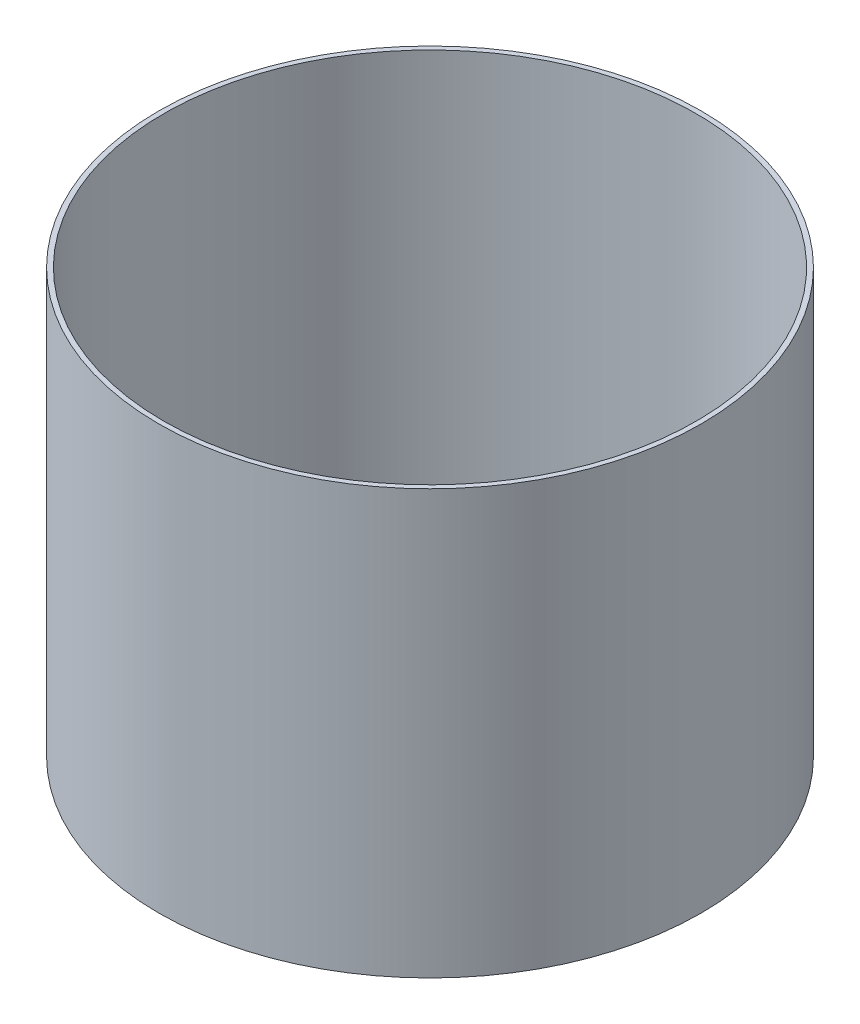
SolidWorks part; units mm, degrees
ref_plane "Front Plane" through (0, 0, 0) normal (0, 0, 1) x (1, 0, 0)
ref_plane "Top Plane" through (0, 0, 0) normal (0, 1, 0) x (1, 0, 0)
ref_plane "Right Plane" through (0, 0, 0) normal (1, 0, 0) x (0, 0, -1)
sketch "Sketch2" plane through (0, 0, 0) normal (0, 1, 0) x (1, 0, 0)
  circle A0 centre (0, 0) radius 71.12
  circle A1 centre (0, 0) radius 69.85
  dimension "D1" = 142.24
  dimension "D2" = 139.7
extrude "Extrude1" add sketch "Sketch2" against normal blind 111.125
sketch "Sketch1" plane through (0, 0, 0) normal (0, 0, 1) x (1, 0, 0)
  line L1 (-228.6, 0) -> (228.6, 0)
  line L2 (-228.6, 0) -> (-228.6, -99.6718)
  line L3 (-228.6, -99.6718) -> (228.6, -99.6718)
  line L4 (228.6, 0) -> (228.6, -99.6718)
  line L416 (-215.864, -82.9078) -> (215.864, -82.9078) construction
  line L417 (215.864, -82.9078) -> (215.864, -66.7382) construction
  line L418 (215.864, -66.7382) -> (-215.864, -66.7382) construction
  line L419 (-215.864, -66.7382) -> (-215.864, -82.9078) construction
  line L420 (-202.6925, -66.7382) -> (-201.5763, -66.7382) construction
  line L421 (-201.5763, -66.7382) -> (-201.5763, -57.5942) construction
  line L422 (-201.5763, -57.5942) -> (-202.6925, -57.5942) construction
  line L423 (-202.6925, -57.5942) -> (-202.6925, -66.7382) construction
  line L424 (-175.7412, -66.7382) -> (-174.6251, -66.7382) construction
  line L425 (-174.6251, -66.7382) -> (-174.6251, -57.5942) construction
  line L426 (-174.6251, -57.5942) -> (-175.7412, -57.5942) construction
  line L427 (-175.7412, -57.5942) -> (-175.7412, -66.7382) construction
  line L428 (-148.79, -66.7382) -> (-147.6738, -66.7382) construction
  line L429 (-147.6738, -66.7382) -> (-147.6738, -57.5942) construction
  line L430 (-147.6738, -57.5942) -> (-148.79, -57.5942) construction
  line L431 (-148.79, -57.5942) -> (-148.79, -66.7382) construction
  line L432 (-121.8387, -66.7382) -> (-120.7225, -66.7382) construction
  line L433 (-120.7225, -66.7382) -> (-120.7225, -57.5942) construction
  line L434 (-120.7225, -57.5942) -> (-121.8387, -57.5942) construction
  line L435 (-121.8387, -57.5942) -> (-121.8387, -66.7382) construction
  line L436 (-94.8875, -66.7382) -> (-93.7713, -66.7382) construction
  line L437 (-93.7713, -66.7382) -> (-93.7713, -57.5942) construction
  line L438 (-93.7713, -57.5942) -> (-94.8875, -57.5942) construction
  line L439 (-94.8875, -57.5942) -> (-94.8875, -66.7382) construction
  line L440 (-67.9362, -66.7382) -> (-66.82, -66.7382) construction
  line L441 (-66.82, -66.7382) -> (-66.82, -57.5942) construction
  line L442 (-66.82, -57.5942) -> (-67.9362, -57.5942) construction
  line L443 (-67.9362, -57.5942) -> (-67.9362, -66.7382) construction
  line L444 (-40.985, -66.7382) -> (-39.8688, -66.7382) construction
  line L445 (-39.8688, -66.7382) -> (-39.8688, -57.5942) construction
  line L446 (-39.8688, -57.5942) -> (-40.985, -57.5942) construction
  line L447 (-40.985, -57.5942) -> (-40.985, -66.7382) construction
  line L448 (-14.0337, -66.7382) -> (-12.9175, -66.7382) construction
  line L449 (-12.9175, -66.7382) -> (-12.9175, -57.5942) construction
  line L450 (-12.9175, -57.5942) -> (-14.0337, -57.5942) construction
  line L451 (-14.0337, -57.5942) -> (-14.0337, -66.7382) construction
  line L452 (12.9175, -66.7382) -> (14.0337, -66.7382) construction
  line L453 (14.0337, -66.7382) -> (14.0337, -57.5942) construction
  line L454 (14.0337, -57.5942) -> (12.9175, -57.5942) construction
  line L455 (12.9175, -57.5942) -> (12.9175, -66.7382) construction
  line L456 (39.8688, -66.7382) -> (40.985, -66.7382) construction
  line L457 (40.985, -66.7382) -> (40.985, -57.5942) construction
  line L458 (40.985, -57.5942) -> (39.8688, -57.5942) construction
  line L459 (39.8688, -57.5942) -> (39.8688, -66.7382) construction
  line L460 (66.82, -66.7382) -> (67.9362, -66.7382) construction
  line L461 (67.9362, -66.7382) -> (67.9362, -57.5942) construction
  line L462 (67.9362, -57.5942) -> (66.82, -57.5942) construction
  line L463 (66.82, -57.5942) -> (66.82, -66.7382) construction
  line L464 (93.7713, -66.7382) -> (94.8875, -66.7382) construction
  line L465 (94.8875, -66.7382) -> (94.8875, -57.5942) construction
  line L466 (94.8875, -57.5942) -> (93.7713, -57.5942) construction
  line L467 (93.7713, -57.5942) -> (93.7713, -66.7382) construction
  line L468 (120.7225, -66.7382) -> (121.8387, -66.7382) construction
  line L469 (121.8387, -66.7382) -> (121.8387, -57.5942) construction
  line L470 (121.8387, -57.5942) -> (120.7225, -57.5942) construction
  line L471 (120.7225, -57.5942) -> (120.7225, -66.7382) construction
  line L472 (147.6738, -66.7382) -> (148.79, -66.7382) construction
  line L473 (148.79, -66.7382) -> (148.79, -57.5942) construction
  line L474 (148.79, -57.5942) -> (147.6738, -57.5942) construction
  line L475 (147.6738, -57.5942) -> (147.6738, -66.7382) construction
  line L476 (174.6251, -66.7382) -> (175.7412, -66.7382) construction
  line L477 (175.7412, -66.7382) -> (175.7412, -57.5942) construction
  line L478 (175.7412, -57.5942) -> (174.6251, -57.5942) construction
  line L479 (174.6251, -57.5942) -> (174.6251, -66.7382) construction
  line L480 (201.5763, -66.7382) -> (202.6925, -66.7382) construction
  line L481 (202.6925, -66.7382) -> (202.6925, -57.5942) construction
  line L482 (202.6925, -57.5942) -> (201.5763, -57.5942) construction
  line L483 (201.5763, -57.5942) -> (201.5763, -66.7382) construction
  line L484 (-201.5763, -57.5942) -> (-175.7412, -57.5942) construction
  line L485 (-175.7412, -57.5942) -> (-175.7412, -56.478) construction
  line L486 (-175.7412, -56.478) -> (-201.5763, -56.478) construction
  line L487 (-201.5763, -56.478) -> (-201.5763, -57.5942) construction
  line L488 (-147.6738, -57.5942) -> (-121.8387, -57.5942) construction
  line L489 (-121.8387, -57.5942) -> (-121.8387, -56.478) construction
  line L490 (-121.8387, -56.478) -> (-147.6738, -56.478) construction
  line L491 (-147.6738, -56.478) -> (-147.6738, -57.5942) construction
  line L492 (-93.7713, -57.5942) -> (-67.9361, -57.5942) construction
  line L493 (-67.9361, -57.5942) -> (-67.9361, -56.478) construction
  line L494 (-67.9361, -56.478) -> (-93.7713, -56.478) construction
  line L495 (-93.7713, -56.478) -> (-93.7713, -57.5942) construction
  line L496 (-39.8687, -57.5942) -> (-14.0336, -57.5942) construction
  line L497 (-14.0336, -57.5942) -> (-14.0336, -56.478) construction
  line L498 (-14.0336, -56.478) -> (-39.8687, -56.478) construction
  line L499 (-39.8687, -56.478) -> (-39.8687, -57.5942) construction
  line L500 (14.0336, -57.5942) -> (39.8687, -57.5942) construction
  line L501 (39.8687, -57.5942) -> (39.8687, -56.478) construction
  line L502 (39.8687, -56.478) -> (14.0336, -56.478) construction
  line L503 (14.0336, -56.478) -> (14.0336, -57.5942) construction
  line L504 (67.9361, -57.5942) -> (93.7713, -57.5942) construction
  line L505 (93.7713, -57.5942) -> (93.7713, -56.478) construction
  line L506 (93.7713, -56.478) -> (67.9361, -56.478) construction
  line L507 (67.9361, -56.478) -> (67.9361, -57.5942) construction
  line L508 (121.8387, -57.5942) -> (147.6738, -57.5942) construction
  line L509 (147.6738, -57.5942) -> (147.6738, -56.478) construction
  line L510 (147.6738, -56.478) -> (121.8387, -56.478) construction
  line L511 (121.8387, -56.478) -> (121.8387, -57.5942) construction
  line L512 (175.7412, -57.5942) -> (201.5763, -57.5942) construction
  line L513 (201.5763, -57.5942) -> (201.5763, -56.478) construction
  line L514 (201.5763, -56.478) -> (175.7412, -56.478) construction
  line L515 (175.7412, -56.478) -> (175.7412, -57.5942) construction
  line L516 (-190.8513, -57.5942) -> (-186.4661, -57.5942) construction
  line L517 (-186.4661, -57.5942) -> (-186.4661, -47.334) construction
  line L518 (-186.4661, -47.334) -> (-190.8513, -47.334) construction
  line L519 (-190.8513, -47.334) -> (-190.8513, -57.5942) construction
  line L520 (-136.9488, -57.5942) -> (-132.5636, -57.5942) construction
  line L521 (-132.5636, -57.5942) -> (-132.5636, -47.334) construction
  line L522 (-132.5636, -47.334) -> (-136.9488, -47.334) construction
  line L523 (-136.9488, -47.334) -> (-136.9488, -57.5942) construction
  line L524 (-83.0464, -57.5942) -> (-78.6611, -57.5942) construction
  line L525 (-78.6611, -57.5942) -> (-78.6611, -47.334) construction
  line L526 (-78.6611, -47.334) -> (-83.0464, -47.334) construction
  line L527 (-83.0464, -47.334) -> (-83.0464, -57.5942) construction
  line L528 (-29.1439, -57.5942) -> (-24.7585, -57.5942) construction
  line L529 (-24.7585, -57.5942) -> (-24.7585, -47.334) construction
  line L530 (-24.7585, -47.334) -> (-29.1439, -47.334) construction
  line L531 (-29.1439, -47.334) -> (-29.1439, -57.5942) construction
  line L532 (24.7585, -57.5942) -> (29.1439, -57.5942) construction
  line L533 (29.1439, -57.5942) -> (29.1439, -47.334) construction
  line L534 (29.1439, -47.334) -> (24.7585, -47.334) construction
  line L535 (24.7585, -47.334) -> (24.7585, -57.5942) construction
  line L536 (78.6611, -57.5942) -> (83.0464, -57.5942) construction
  line L537 (83.0464, -57.5942) -> (83.0464, -47.334) construction
  line L538 (83.0464, -47.334) -> (78.6611, -47.334) construction
  line L539 (78.6611, -47.334) -> (78.6611, -57.5942) construction
  line L540 (132.5636, -57.5942) -> (136.9488, -57.5942) construction
  line L541 (136.9488, -57.5942) -> (136.9488, -47.334) construction
  line L542 (136.9488, -47.334) -> (132.5636, -47.334) construction
  line L543 (132.5636, -47.334) -> (132.5636, -57.5942) construction
  line L544 (186.4661, -57.5942) -> (190.8513, -57.5942) construction
  line L545 (190.8513, -57.5942) -> (190.8513, -47.334) construction
  line L546 (190.8513, -47.334) -> (186.4661, -47.334) construction
  line L547 (186.4661, -47.334) -> (186.4661, -57.5942) construction
  line L548 (-186.466, -47.334) -> (-177.9096, -47.334) construction
  line L549 (-177.9096, -47.334) -> (-177.9096, -42.9487) construction
  line L550 (-177.9096, -42.9487) -> (-186.466, -42.9487) construction
  line L551 (-186.466, -42.9487) -> (-186.466, -47.334) construction
  line L552 (-145.5055, -47.334) -> (-136.9489, -47.334) construction
  line L553 (-136.9489, -47.334) -> (-136.9489, -42.9487) construction
  line L554 (-136.9489, -42.9487) -> (-145.5055, -42.9487) construction
  line L555 (-145.5055, -42.9487) -> (-145.5055, -47.334) construction
  line L556 (-78.6611, -47.334) -> (-70.1045, -47.334) construction
  line L557 (-70.1045, -47.334) -> (-70.1045, -42.9487) construction
  line L558 (-70.1045, -42.9487) -> (-78.6611, -42.9487) construction
  line L559 (-78.6611, -42.9487) -> (-78.6611, -47.334) construction
  line L560 (-37.7005, -47.334) -> (-29.1439, -47.334) construction
  line L561 (-29.1439, -47.334) -> (-29.1439, -42.9487) construction
  line L562 (-29.1439, -42.9487) -> (-37.7005, -42.9487) construction
  line L563 (-37.7005, -42.9487) -> (-37.7005, -47.334) construction
  line L564 (29.1439, -47.334) -> (37.7005, -47.334) construction
  line L565 (37.7005, -47.334) -> (37.7005, -42.9487) construction
  line L566 (37.7005, -42.9487) -> (29.1439, -42.9487) construction
  line L567 (29.1439, -42.9487) -> (29.1439, -47.334) construction
  line L568 (70.1045, -47.334) -> (78.6611, -47.334) construction
  line L569 (78.6611, -47.334) -> (78.6611, -42.9487) construction
  line L570 (78.6611, -42.9487) -> (70.1045, -42.9487) construction
  line L571 (70.1045, -42.9487) -> (70.1045, -47.334) construction
  line L572 (136.9489, -47.334) -> (145.5055, -47.334) construction
  line L573 (145.5055, -47.334) -> (145.5055, -42.9487) construction
  line L574 (145.5055, -42.9487) -> (136.9489, -42.9487) construction
  line L575 (136.9489, -42.9487) -> (136.9489, -47.334) construction
  line L576 (177.9096, -47.334) -> (186.466, -47.334) construction
  line L577 (186.466, -47.334) -> (186.466, -42.9487) construction
  line L578 (186.466, -42.9487) -> (177.9096, -42.9487) construction
  line L579 (177.9096, -42.9487) -> (177.9096, -47.334) construction
  line L580 (-177.9095, -46.538) -> (-168.0714, -46.538) construction
  line L581 (-168.0714, -46.538) -> (-168.0714, -43.7446) construction
  line L582 (-168.0714, -43.7446) -> (-177.9095, -43.7446) construction
  line L583 (-177.9095, -43.7446) -> (-177.9095, -46.538) construction
  line L584 (-155.3435, -46.538) -> (-145.5054, -46.538) construction
  line L585 (-145.5054, -46.538) -> (-145.5054, -43.7446) construction
  line L586 (-145.5054, -43.7446) -> (-155.3435, -43.7446) construction
  line L587 (-155.3435, -43.7446) -> (-155.3435, -46.538) construction
  line L588 (-70.1045, -46.538) -> (-60.2665, -46.538) construction
  line L589 (-60.2665, -46.538) -> (-60.2665, -43.7446) construction
  line L590 (-60.2665, -43.7446) -> (-70.1045, -43.7446) construction
  line L591 (-70.1045, -43.7446) -> (-70.1045, -46.538) construction
  line L592 (-47.5385, -46.538) -> (-37.7005, -46.538) construction
  line L593 (-37.7005, -46.538) -> (-37.7005, -43.7446) construction
  line L594 (-37.7005, -43.7446) -> (-47.5385, -43.7446) construction
  line L595 (-47.5385, -43.7446) -> (-47.5385, -46.538) construction
  line L596 (37.7005, -46.538) -> (47.5385, -46.538) construction
  line L597 (47.5385, -46.538) -> (47.5385, -43.7446) construction
  line L598 (47.5385, -43.7446) -> (37.7005, -43.7446) construction
  line L599 (37.7005, -43.7446) -> (37.7005, -46.538) construction
  line L600 (60.2665, -46.538) -> (70.1045, -46.538) construction
  line L601 (70.1045, -46.538) -> (70.1045, -43.7446) construction
  line L602 (70.1045, -43.7446) -> (60.2665, -43.7446) construction
  line L603 (60.2665, -43.7446) -> (60.2665, -46.538) construction
  line L604 (145.5054, -46.538) -> (155.3435, -46.538) construction
  line L605 (155.3435, -46.538) -> (155.3435, -43.7446) construction
  line L606 (155.3435, -43.7446) -> (145.5054, -43.7446) construction
  line L607 (145.5054, -43.7446) -> (145.5054, -46.538) construction
  line L608 (168.0714, -46.538) -> (177.9095, -46.538) construction
  line L609 (177.9095, -46.538) -> (177.9095, -43.7446) construction
  line L610 (177.9095, -43.7446) -> (168.0714, -43.7446) construction
  line L611 (168.0714, -43.7446) -> (168.0714, -46.538) construction
  line L612 (-168.0714, -45.9607) -> (-155.3436, -45.9607) construction
  line L613 (-155.3436, -45.9607) -> (-155.3436, -44.322) construction
  line L614 (-155.3436, -44.322) -> (-168.0714, -44.322) construction
  line L615 (-168.0714, -44.322) -> (-168.0714, -45.9607) construction
  line L616 (-60.2665, -45.9607) -> (-47.5385, -45.9607) construction
  line L617 (-47.5385, -45.9607) -> (-47.5385, -44.322) construction
  line L618 (-47.5385, -44.322) -> (-60.2665, -44.322) construction
  line L619 (-60.2665, -44.322) -> (-60.2665, -45.9607) construction
  line L620 (47.5385, -45.9607) -> (60.2665, -45.9607) construction
  line L621 (60.2665, -45.9607) -> (60.2665, -44.322) construction
  line L622 (60.2665, -44.322) -> (47.5385, -44.322) construction
  line L623 (47.5385, -44.322) -> (47.5385, -45.9607) construction
  line L624 (155.3436, -45.9607) -> (168.0714, -45.9607) construction
  line L625 (168.0714, -45.9607) -> (168.0714, -44.322) construction
  line L626 (168.0714, -44.322) -> (155.3436, -44.322) construction
  line L627 (155.3436, -44.322) -> (155.3436, -45.9607) construction
  line L628 (-164.5244, -44.322) -> (-158.8906, -44.322) construction
  line L629 (-158.8906, -44.322) -> (-158.8906, -35.178) construction
  line L630 (-158.8906, -35.178) -> (-164.5244, -35.178) construction
  line L631 (-164.5244, -35.178) -> (-164.5244, -44.322) construction
  line L632 (-56.7194, -44.322) -> (-51.0856, -44.322) construction
  line L633 (-51.0856, -44.322) -> (-51.0856, -35.178) construction
  line L634 (-51.0856, -35.178) -> (-56.7194, -35.178) construction
  line L635 (-56.7194, -35.178) -> (-56.7194, -44.322) construction
  line L636 (51.0856, -44.322) -> (56.7194, -44.322) construction
  line L637 (56.7194, -44.322) -> (56.7194, -35.178) construction
  line L638 (56.7194, -35.178) -> (51.0856, -35.178) construction
  line L639 (51.0856, -35.178) -> (51.0856, -44.322) construction
  line L640 (158.8906, -44.322) -> (164.5244, -44.322) construction
  line L641 (164.5244, -44.322) -> (164.5244, -35.178) construction
  line L642 (164.5244, -35.178) -> (158.8906, -35.178) construction
  line L643 (158.8906, -35.178) -> (158.8906, -44.322) construction
  line L644 (-158.8906, -35.178) -> (-131.3922, -35.178) construction
  line L645 (-131.3922, -35.178) -> (-131.3922, -29.5443) construction
  line L646 (-131.3922, -29.5443) -> (-158.8906, -29.5443) construction
  line L647 (-158.8906, -29.5443) -> (-158.8906, -35.178) construction
  line L648 (-84.2178, -35.178) -> (-56.7194, -35.178) construction
  line L649 (-56.7194, -35.178) -> (-56.7194, -29.5443) construction
  line L650 (-56.7194, -29.5443) -> (-84.2178, -29.5443) construction
  line L651 (-84.2178, -29.5443) -> (-84.2178, -35.178) construction
  line L652 (56.7194, -35.178) -> (84.2178, -35.178) construction
  line L653 (84.2178, -35.178) -> (84.2178, -29.5443) construction
  line L654 (84.2178, -29.5443) -> (56.7194, -29.5443) construction
  line L655 (56.7194, -29.5443) -> (56.7194, -35.178) construction
  line L656 (131.3922, -35.178) -> (158.8906, -35.178) construction
  line L657 (158.8906, -35.178) -> (158.8906, -29.5443) construction
  line L658 (158.8906, -29.5443) -> (131.3922, -29.5443) construction
  line L659 (131.3922, -29.5443) -> (131.3922, -35.178) construction
  line L660 (-131.3922, -33.9769) -> (-121.3448, -33.9769) construction
  line L661 (-121.3448, -33.9769) -> (-121.3448, -30.7453) construction
  line L662 (-121.3448, -30.7453) -> (-131.3922, -30.7453) construction
  line L663 (-131.3922, -30.7453) -> (-131.3922, -33.9769) construction
  line L664 (-94.2652, -33.9769) -> (-84.2178, -33.9769) construction
  line L665 (-84.2178, -33.9769) -> (-84.2178, -30.7453) construction
  line L666 (-84.2178, -30.7453) -> (-94.2652, -30.7453) construction
  line L667 (-94.2652, -30.7453) -> (-94.2652, -33.9769) construction
  line L668 (84.2178, -33.9769) -> (94.2652, -33.9769) construction
  line L669 (94.2652, -33.9769) -> (94.2652, -30.7453) construction
  line L670 (94.2652, -30.7453) -> (84.2178, -30.7453) construction
  line L671 (84.2178, -30.7453) -> (84.2178, -33.9769) construction
  line L672 (121.3448, -33.9769) -> (131.3922, -33.9769) construction
  line L673 (131.3922, -33.9769) -> (131.3922, -30.7453) construction
  line L674 (131.3922, -30.7453) -> (121.3448, -30.7453) construction
  line L675 (121.3448, -30.7453) -> (121.3448, -33.9769) construction
  line L676 (-121.3448, -33.1804) -> (-94.2652, -33.1804) construction
  line L677 (-94.2652, -33.1804) -> (-94.2652, -31.5418) construction
  line L678 (-94.2652, -31.5418) -> (-121.3448, -31.5418) construction
  line L679 (-121.3448, -31.5418) -> (-121.3448, -33.1804) construction
  line L680 (94.2652, -33.1804) -> (121.3448, -33.1804) construction
  line L681 (121.3448, -33.1804) -> (121.3448, -31.5418) construction
  line L682 (121.3448, -31.5418) -> (94.2652, -31.5418) construction
  line L683 (94.2652, -31.5418) -> (94.2652, -33.1804) construction
  line L684 (-110.6219, -31.5418) -> (-104.9881, -31.5418) construction
  line L685 (-104.9881, -31.5418) -> (-104.9881, -22.3978) construction
  line L686 (-104.9881, -22.3978) -> (-110.6219, -22.3978) construction
  line L687 (-110.6219, -22.3978) -> (-110.6219, -31.5418) construction
  line L688 (104.9881, -31.5418) -> (110.6219, -31.5418) construction
  line L689 (110.6219, -31.5418) -> (110.6219, -22.3978) construction
  line L690 (110.6219, -22.3978) -> (104.9881, -22.3978) construction
  line L691 (104.9881, -22.3978) -> (104.9881, -31.5418) construction
  line L692 (-104.9881, -22.3978) -> (-41.5547, -22.3978) construction
  line L693 (-41.5547, -22.3978) -> (-41.5547, -16.764) construction
  line L694 (-41.5547, -16.764) -> (-104.9881, -16.764) construction
  line L695 (-104.9881, -16.764) -> (-104.9881, -22.3978) construction
  line L696 (41.5547, -22.3978) -> (104.9881, -22.3978) construction
  line L697 (104.9881, -22.3978) -> (104.9881, -16.764) construction
  line L698 (104.9881, -16.764) -> (41.5547, -16.764) construction
  line L699 (41.5547, -16.764) -> (41.5547, -22.3978) construction
  line L700 (-41.5547, -21.1967) -> (-31.5072, -21.1967) construction
  line L701 (-31.5072, -21.1967) -> (-31.5072, -17.9651) construction
  line L702 (-31.5072, -17.9651) -> (-41.5547, -17.9651) construction
  line L703 (-41.5547, -17.9651) -> (-41.5547, -21.1967) construction
  line L704 (31.5072, -21.1967) -> (41.5547, -21.1967) construction
  line L705 (41.5547, -21.1967) -> (41.5547, -17.9651) construction
  line L706 (41.5547, -17.9651) -> (31.5072, -17.9651) construction
  line L707 (31.5072, -17.9651) -> (31.5072, -21.1967) construction
  line L708 (-31.5073, -20.4003) -> (31.5073, -20.4003) construction
  line L709 (31.5073, -20.4003) -> (31.5073, -18.7616) construction
  line L710 (31.5073, -18.7616) -> (-31.5073, -18.7616) construction
  line L711 (-31.5073, -18.7616) -> (-31.5073, -20.4003) construction
  line L712 (-202.1344, -57.5942) -> (-201.5762, -57.5942) construction
  line L713 (-201.5762, -57.5942) -> (-201.5762, -57.0361) construction
  line L714 (-201.5762, -57.0361) -> (-202.1344, -57.0361) construction
  line L715 (-202.1344, -57.0361) -> (-202.1344, -57.5942) construction
  line L716 (-175.7412, -57.5942) -> (-175.183, -57.5942) construction
  line L717 (-175.183, -57.5942) -> (-175.183, -57.0361) construction
  line L718 (-175.183, -57.0361) -> (-175.7412, -57.0361) construction
  line L719 (-175.7412, -57.0361) -> (-175.7412, -57.5942) construction
  line L720 (-148.2319, -57.5942) -> (-147.6737, -57.5942) construction
  line L721 (-147.6737, -57.5942) -> (-147.6737, -57.0361) construction
  line L722 (-147.6737, -57.0361) -> (-148.2319, -57.0361) construction
  line L723 (-148.2319, -57.0361) -> (-148.2319, -57.5942) construction
  line L724 (-121.8387, -57.5942) -> (-121.2806, -57.5942) construction
  line L725 (-121.2806, -57.5942) -> (-121.2806, -57.0361) construction
  line L726 (-121.2806, -57.0361) -> (-121.8387, -57.0361) construction
  line L727 (-121.8387, -57.0361) -> (-121.8387, -57.5942) construction
  line L728 (-94.3293, -57.5942) -> (-93.7712, -57.5942) construction
  line L729 (-93.7712, -57.5942) -> (-93.7712, -57.0361) construction
  line L730 (-93.7712, -57.0361) -> (-94.3293, -57.0361) construction
  line L731 (-94.3293, -57.0361) -> (-94.3293, -57.5942) construction
  line L732 (-67.9361, -57.5942) -> (-67.3781, -57.5942) construction
  line L733 (-67.3781, -57.5942) -> (-67.3781, -57.0361) construction
  line L734 (-67.3781, -57.0361) -> (-67.9361, -57.0361) construction
  line L735 (-67.9361, -57.0361) -> (-67.9361, -57.5942) construction
  line L736 (-40.4268, -57.5942) -> (-39.8687, -57.5942) construction
  line L737 (-39.8687, -57.5942) -> (-39.8687, -57.0361) construction
  line L738 (-39.8687, -57.0361) -> (-40.4268, -57.0361) construction
  line L739 (-40.4268, -57.0361) -> (-40.4268, -57.5942) construction
  line L740 (-14.0336, -57.5942) -> (-13.4756, -57.5942) construction
  line L741 (-13.4756, -57.5942) -> (-13.4756, -57.0361) construction
  line L742 (-13.4756, -57.0361) -> (-14.0336, -57.0361) construction
  line L743 (-14.0336, -57.0361) -> (-14.0336, -57.5942) construction
  line L744 (13.4756, -57.5942) -> (14.0336, -57.5942) construction
  line L745 (14.0336, -57.5942) -> (14.0336, -57.0361) construction
  line L746 (14.0336, -57.0361) -> (13.4756, -57.0361) construction
  line L747 (13.4756, -57.0361) -> (13.4756, -57.5942) construction
  line L748 (39.8687, -57.5942) -> (40.4268, -57.5942) construction
  line L749 (40.4268, -57.5942) -> (40.4268, -57.0361) construction
  line L750 (40.4268, -57.0361) -> (39.8687, -57.0361) construction
  line L751 (39.8687, -57.0361) -> (39.8687, -57.5942) construction
  line L752 (67.3781, -57.5942) -> (67.9361, -57.5942) construction
  line L753 (67.9361, -57.5942) -> (67.9361, -57.0361) construction
  line L754 (67.9361, -57.0361) -> (67.3781, -57.0361) construction
  line L755 (67.3781, -57.0361) -> (67.3781, -57.5942) construction
  line L756 (93.7712, -57.5942) -> (94.3293, -57.5942) construction
  line L757 (94.3293, -57.5942) -> (94.3293, -57.0361) construction
  line L758 (94.3293, -57.0361) -> (93.7712, -57.0361) construction
  line L759 (93.7712, -57.0361) -> (93.7712, -57.5942) construction
  line L760 (121.2806, -57.5942) -> (121.8387, -57.5942) construction
  line L761 (121.8387, -57.5942) -> (121.8387, -57.0361) construction
  line L762 (121.8387, -57.0361) -> (121.2806, -57.0361) construction
  line L763 (121.2806, -57.0361) -> (121.2806, -57.5942) construction
  line L764 (147.6737, -57.5942) -> (148.2319, -57.5942) construction
  line L765 (148.2319, -57.5942) -> (148.2319, -57.0361) construction
  line L766 (148.2319, -57.0361) -> (147.6737, -57.0361) construction
  line L767 (147.6737, -57.0361) -> (147.6737, -57.5942) construction
  line L768 (175.183, -57.5942) -> (175.7412, -57.5942) construction
  line L769 (175.7412, -57.5942) -> (175.7412, -57.0361) construction
  line L770 (175.7412, -57.0361) -> (175.183, -57.0361) construction
  line L771 (175.183, -57.0361) -> (175.183, -57.5942) construction
  line L772 (201.5762, -57.5942) -> (202.1344, -57.5942) construction
  line L773 (202.1344, -57.5942) -> (202.1344, -57.0361) construction
  line L774 (202.1344, -57.0361) -> (201.5762, -57.0361) construction
  line L775 (201.5762, -57.0361) -> (201.5762, -57.5942) construction
  line L776 (-188.6588, -47.334) -> (-186.466, -47.334) construction
  line L777 (-186.466, -47.334) -> (-186.466, -45.1412) construction
  line L778 (-186.466, -45.1412) -> (-188.6588, -45.1412) construction
  line L779 (-188.6588, -45.1412) -> (-188.6588, -47.334) construction
  line L780 (-136.9489, -47.334) -> (-134.7563, -47.334) construction
  line L781 (-134.7563, -47.334) -> (-134.7563, -45.1412) construction
  line L782 (-134.7563, -45.1412) -> (-136.9489, -45.1412) construction
  line L783 (-136.9489, -45.1412) -> (-136.9489, -47.334) construction
  line L784 (-80.8538, -47.334) -> (-78.6611, -47.334) construction
  line L785 (-78.6611, -47.334) -> (-78.6611, -45.1412) construction
  line L786 (-78.6611, -45.1412) -> (-80.8538, -45.1412) construction
  line L787 (-80.8538, -45.1412) -> (-80.8538, -47.334) construction
  line L788 (-29.1439, -47.334) -> (-26.9513, -47.334) construction
  line L789 (-26.9513, -47.334) -> (-26.9513, -45.1412) construction
  line L790 (-26.9513, -45.1412) -> (-29.1439, -45.1412) construction
  line L791 (-29.1439, -45.1412) -> (-29.1439, -47.334) construction
  line L792 (26.9513, -47.334) -> (29.1439, -47.334) construction
  line L793 (29.1439, -47.334) -> (29.1439, -45.1412) construction
  line L794 (29.1439, -45.1412) -> (26.9513, -45.1412) construction
  line L795 (26.9513, -45.1412) -> (26.9513, -47.334) construction
  line L796 (78.6611, -47.334) -> (80.8538, -47.334) construction
  line L797 (80.8538, -47.334) -> (80.8538, -45.1412) construction
  line L798 (80.8538, -45.1412) -> (78.6611, -45.1412) construction
  line L799 (78.6611, -45.1412) -> (78.6611, -47.334) construction
  line L800 (134.7563, -47.334) -> (136.9489, -47.334) construction
  line L801 (136.9489, -47.334) -> (136.9489, -45.1412) construction
  line L802 (136.9489, -45.1412) -> (134.7563, -45.1412) construction
  line L803 (134.7563, -45.1412) -> (134.7563, -47.334) construction
  line L804 (186.466, -47.334) -> (188.6588, -47.334) construction
  line L805 (188.6588, -47.334) -> (188.6588, -45.1412) construction
  line L806 (188.6588, -45.1412) -> (186.466, -45.1412) construction
  line L807 (186.466, -45.1412) -> (186.466, -47.334) construction
  line L808 (-161.7074, -35.178) -> (-158.8906, -35.178) construction
  line L809 (-158.8906, -35.178) -> (-158.8906, -32.3611) construction
  line L810 (-158.8906, -32.3611) -> (-161.7074, -32.3611) construction
  line L811 (-161.7074, -32.3611) -> (-161.7074, -35.178) construction
  line L812 (-56.7193, -35.178) -> (-53.9024, -35.178) construction
  line L813 (-53.9024, -35.178) -> (-53.9024, -32.3611) construction
  line L814 (-53.9024, -32.3611) -> (-56.7193, -32.3611) construction
  line L815 (-56.7193, -32.3611) -> (-56.7193, -35.178) construction
  line L816 (53.9024, -35.178) -> (56.7193, -35.178) construction
  line L817 (56.7193, -35.178) -> (56.7193, -32.3611) construction
  line L818 (56.7193, -32.3611) -> (53.9024, -32.3611) construction
  line L819 (53.9024, -32.3611) -> (53.9024, -35.178) construction
  line L820 (158.8906, -35.178) -> (161.7074, -35.178) construction
  line L821 (161.7074, -35.178) -> (161.7074, -32.3611) construction
  line L822 (161.7074, -32.3611) -> (158.8906, -32.3611) construction
  line L823 (158.8906, -32.3611) -> (158.8906, -35.178) construction
  line L824 (-107.805, -22.3977) -> (-104.9881, -22.3977) construction
  line L825 (-104.9881, -22.3977) -> (-104.9881, -19.5809) construction
  line L826 (-104.9881, -19.5809) -> (-107.805, -19.5809) construction
  line L827 (-107.805, -19.5809) -> (-107.805, -22.3977) construction
  line L828 (104.9881, -22.3977) -> (107.805, -22.3977) construction
  line L829 (107.805, -22.3977) -> (107.805, -19.5809) construction
  line L830 (107.805, -19.5809) -> (104.9881, -19.5809) construction
  line L831 (104.9881, -19.5809) -> (104.9881, -22.3977) construction
  line L832 (-228.6, 0) -> (228.6, 0) construction
  line L866 (-228.6, -99.6718) -> (228.6, -99.6718) construction
  line L867 (-228.6, 0) -> (228.6, 0) construction
  line L868 (218.15, -9.144) -> (218.15, -57.5942) construction
  line L869 (-218.15, -9.144) -> (-218.15, -57.5942) construction
  line L870 (-202.4134, -57.5942) -> (-201.5763, -56.757) construction
  line L871 (-175.7412, -56.757) -> (-174.9041, -57.5942) construction
  line L872 (-148.5109, -57.5942) -> (-147.6738, -56.757) construction
  line L873 (-121.8387, -56.757) -> (-121.0016, -57.5942) construction
  line L874 (-94.6084, -57.5942) -> (-93.7713, -56.757) construction
  line L875 (-67.9362, -56.757) -> (-67.0991, -57.5942) construction
  line L876 (-40.7059, -57.5942) -> (-39.8688, -56.757) construction
  line L877 (-14.0337, -56.757) -> (-13.1966, -57.5942) construction
  line L878 (13.1966, -57.5942) -> (14.0337, -56.757) construction
  line L879 (39.8688, -56.757) -> (40.7059, -57.5942) construction
  line L880 (67.0991, -57.5942) -> (67.9362, -56.757) construction
  line L881 (93.7713, -56.757) -> (94.6084, -57.5942) construction
  line L882 (121.0016, -57.5942) -> (121.8387, -56.757) construction
  line L883 (147.6738, -56.757) -> (148.5109, -57.5942) construction
  line L884 (174.9041, -57.5942) -> (175.7412, -56.757) construction
  line L885 (201.5763, -56.757) -> (202.4134, -57.5942) construction
  line L886 (-189.7551, -47.334) -> (-186.4661, -44.045) construction
  line L887 (-136.9489, -44.045) -> (-133.66, -47.334) construction
  line L888 (-81.9501, -47.334) -> (-78.6611, -44.045) construction
  line L889 (-29.1439, -44.045) -> (-25.8549, -47.334) construction
  line L890 (25.8549, -47.334) -> (29.1439, -44.045) construction
  line L891 (78.6611, -44.045) -> (81.9501, -47.334) construction
  line L892 (133.66, -47.334) -> (136.9489, -44.045) construction
  line L893 (186.4661, -44.045) -> (189.7551, -47.334) construction
  line L894 (-163.116, -35.178) -> (-158.8906, -30.9527) construction
  line L895 (-56.7194, -30.9527) -> (-52.4941, -35.178) construction
  line L896 (52.4941, -35.178) -> (56.7194, -30.9527) construction
  line L897 (158.8906, -30.9527) -> (163.116, -35.178) construction
  line L898 (-109.2134, -22.3978) -> (-104.9881, -18.1725) construction
  line L899 (104.9881, -18.1725) -> (109.2134, -22.3978) construction
  circle A25 centre (210.53, -94.5918) radius 2.54 construction
  circle A26 centre (107.805, -94.5918) radius 2.54 construction
  circle A27 centre (0, -94.5918) radius 2.54 construction
  circle A28 centre (-107.805, -94.5918) radius 2.54 construction
  circle A29 centre (-210.53, -94.5918) radius 2.54 construction
  circle A30 centre (210.53, -5.08) radius 2.54 construction
  circle A31 centre (107.805, -5.08) radius 2.54 construction
  circle A32 centre (0, -5.08) radius 2.54 construction
  circle A33 centre (-107.805, -5.08) radius 2.54 construction
  circle A34 centre (-210.53, -5.08) radius 2.54 construction
  circle A35 centre (210.53, -49.8359) radius 2.54 construction
  circle A36 centre (-210.53, -49.8359) radius 2.54 construction
  circle A37 centre (0, -19.5809) radius 6.35 construction
  circle A38 centre (210.53, -94.5918) radius 1.1303 construction
  circle A39 centre (107.805, -94.5918) radius 1.1303 construction
  circle A40 centre (0, -94.5918) radius 1.1303 construction
  circle A41 centre (-107.805, -94.5918) radius 1.1303 construction
  circle A42 centre (-210.53, -94.5918) radius 1.1303 construction
  circle A43 centre (210.53, -5.08) radius 1.1303 construction
  circle A44 centre (107.805, -5.08) radius 1.1303 construction
  circle A45 centre (0, -5.08) radius 1.1303 construction
  circle A46 centre (-107.805, -5.08) radius 1.1303 construction
  circle A47 centre (-210.53, -5.08) radius 1.1303 construction
  circle A48 centre (210.53, -49.8359) radius 1.1303 construction
  circle A49 centre (-210.53, -49.8359) radius 1.1303 construction
  circle A62 centre (210.53, -94.5918) radius 0.635 construction
  circle A63 centre (107.805, -94.5918) radius 0.635 construction
  circle A64 centre (0, -94.5918) radius 0.635 construction
  circle A65 centre (-107.805, -94.5918) radius 0.635 construction
  circle A66 centre (-210.53, -94.5918) radius 0.635 construction
  circle A67 centre (210.53, -5.08) radius 0.635 construction
  circle A68 centre (107.805, -5.08) radius 0.635 construction
  circle A69 centre (0, -5.08) radius 0.635 construction
  circle A70 centre (-107.805, -5.08) radius 0.635 construction
  circle A71 centre (-210.53, -5.08) radius 0.635 construction
  circle A72 centre (210.53, -49.8359) radius 0.635 construction
  circle A73 centre (-210.53, -49.8359) radius 0.635 construction
  circle A144 centre (0, -19.5809) radius 0.4762 construction
  circle A145 centre (0, -19.5809) radius 0.4762 construction
  arc A147 (-228.6, -99.6083) -> (-228.6, -99.7353) centre (-228.6, -99.6718) ccw construction
  arc A150 (217.515, -57.5942) -> (218.785, -57.5942) centre (218.15, -57.5942) ccw construction
  arc A151 (218.785, -9.144) -> (217.515, -9.144) centre (218.15, -9.144) ccw construction
  arc A152 (-218.785, -57.5942) -> (-217.515, -57.5942) centre (-218.15, -57.5942) ccw construction
  arc A153 (-217.515, -9.144) -> (-218.785, -9.144) centre (-218.15, -9.144) ccw construction
  arc A154 (-201.4777, -56.8556) -> (-201.6749, -56.6584) centre (-201.5763, -56.757) ccw construction
  arc A155 (-202.512, -57.4956) -> (-202.3148, -57.6928) centre (-202.4134, -57.5942) ccw construction
  arc A156 (-175.0027, -57.6928) -> (-174.8055, -57.4956) centre (-174.9041, -57.5942) ccw construction
  arc A157 (-175.6426, -56.6584) -> (-175.8398, -56.8556) centre (-175.7412, -56.757) ccw construction
  arc A158 (-147.5752, -56.8556) -> (-147.7724, -56.6584) centre (-147.6738, -56.757) ccw construction
  arc A159 (-148.6095, -57.4956) -> (-148.4123, -57.6928) centre (-148.5109, -57.5942) ccw construction
  arc A160 (-121.1002, -57.6928) -> (-120.903, -57.4956) centre (-121.0016, -57.5942) ccw construction
  arc A161 (-121.7401, -56.6584) -> (-121.9373, -56.8556) centre (-121.8387, -56.757) ccw construction
  arc A162 (-93.6727, -56.8556) -> (-93.8699, -56.6584) centre (-93.7713, -56.757) ccw construction
  arc A163 (-94.707, -57.4956) -> (-94.5098, -57.6928) centre (-94.6084, -57.5942) ccw construction
  arc A164 (-67.1977, -57.6928) -> (-67.0005, -57.4956) centre (-67.0991, -57.5942) ccw construction
  arc A165 (-67.8376, -56.6584) -> (-68.0348, -56.8556) centre (-67.9362, -56.757) ccw construction
  arc A166 (-39.7702, -56.8556) -> (-39.9674, -56.6584) centre (-39.8688, -56.757) ccw construction
  arc A167 (-40.8045, -57.4956) -> (-40.6073, -57.6928) centre (-40.7059, -57.5942) ccw construction
  arc A168 (-13.2952, -57.6928) -> (-13.098, -57.4956) centre (-13.1966, -57.5942) ccw construction
  arc A169 (-13.9351, -56.6584) -> (-14.1323, -56.8556) centre (-14.0337, -56.757) ccw construction
  arc A170 (14.1323, -56.8556) -> (13.9351, -56.6584) centre (14.0337, -56.757) ccw construction
  arc A171 (13.098, -57.4956) -> (13.2952, -57.6928) centre (13.1966, -57.5942) ccw construction
  arc A172 (40.6073, -57.6928) -> (40.8045, -57.4956) centre (40.7059, -57.5942) ccw construction
  arc A173 (39.9674, -56.6584) -> (39.7702, -56.8556) centre (39.8688, -56.757) ccw construction
  arc A174 (68.0348, -56.8556) -> (67.8376, -56.6584) centre (67.9362, -56.757) ccw construction
  arc A175 (67.0005, -57.4956) -> (67.1977, -57.6928) centre (67.0991, -57.5942) ccw construction
  arc A176 (94.5098, -57.6928) -> (94.707, -57.4956) centre (94.6084, -57.5942) ccw construction
  arc A177 (93.8699, -56.6584) -> (93.6727, -56.8556) centre (93.7713, -56.757) ccw construction
  arc A178 (121.9373, -56.8556) -> (121.7401, -56.6584) centre (121.8387, -56.757) ccw construction
  arc A179 (120.903, -57.4956) -> (121.1002, -57.6928) centre (121.0016, -57.5942) ccw construction
  arc A180 (148.4123, -57.6928) -> (148.6095, -57.4956) centre (148.5109, -57.5942) ccw construction
  arc A181 (147.7724, -56.6584) -> (147.5752, -56.8556) centre (147.6738, -56.757) ccw construction
  arc A182 (175.8398, -56.8556) -> (175.6426, -56.6584) centre (175.7412, -56.757) ccw construction
  arc A183 (174.8055, -57.4956) -> (175.0027, -57.6928) centre (174.9041, -57.5942) ccw construction
  arc A184 (202.3148, -57.6928) -> (202.512, -57.4956) centre (202.4134, -57.5942) ccw construction
  arc A185 (201.6749, -56.6584) -> (201.4777, -56.8556) centre (201.5763, -56.757) ccw construction
  arc A186 (-186.0785, -44.4326) -> (-186.8537, -43.6574) centre (-186.4661, -44.045) ccw construction
  arc A187 (-190.1427, -46.9464) -> (-189.3675, -47.7216) centre (-189.7551, -47.334) ccw construction
  arc A188 (-134.0476, -47.7216) -> (-133.2724, -46.9464) centre (-133.66, -47.334) ccw construction
  arc A189 (-136.5613, -43.6574) -> (-137.3365, -44.4326) centre (-136.9489, -44.045) ccw construction
  arc A190 (-78.2735, -44.4326) -> (-79.0487, -43.6574) centre (-78.6611, -44.045) ccw construction
  arc A191 (-82.3377, -46.9464) -> (-81.5625, -47.7216) centre (-81.9501, -47.334) ccw construction
  arc A192 (-26.2425, -47.7216) -> (-25.4673, -46.9464) centre (-25.8549, -47.334) ccw construction
  arc A193 (-28.7563, -43.6574) -> (-29.5315, -44.4326) centre (-29.1439, -44.045) ccw construction
  arc A194 (29.5315, -44.4326) -> (28.7563, -43.6574) centre (29.1439, -44.045) ccw construction
  arc A195 (25.4673, -46.9464) -> (26.2425, -47.7216) centre (25.8549, -47.334) ccw construction
  arc A196 (81.5625, -47.7216) -> (82.3377, -46.9464) centre (81.9501, -47.334) ccw construction
  arc A197 (79.0487, -43.6574) -> (78.2735, -44.4326) centre (78.6611, -44.045) ccw construction
  arc A198 (137.3365, -44.4326) -> (136.5613, -43.6574) centre (136.9489, -44.045) ccw construction
  arc A199 (133.2724, -46.9464) -> (134.0476, -47.7216) centre (133.66, -47.334) ccw construction
  arc A200 (189.3675, -47.7216) -> (190.1427, -46.9464) centre (189.7551, -47.334) ccw construction
  arc A201 (186.8537, -43.6574) -> (186.0785, -44.4326) centre (186.4661, -44.045) ccw construction
  arc A202 (-158.3927, -31.4507) -> (-159.3885, -30.4547) centre (-158.8906, -30.9527) ccw construction
  arc A203 (-163.6139, -34.68) -> (-162.6181, -35.676) centre (-163.116, -35.178) ccw construction
  arc A204 (-52.992, -35.6759) -> (-51.9962, -34.6801) centre (-52.4941, -35.178) ccw construction
  arc A205 (-56.2215, -30.4548) -> (-57.2173, -31.4506) centre (-56.7194, -30.9527) ccw construction
  arc A206 (57.2173, -31.4506) -> (56.2215, -30.4548) centre (56.7194, -30.9527) ccw construction
  arc A207 (51.9962, -34.6801) -> (52.992, -35.6759) centre (52.4941, -35.178) ccw construction
  arc A208 (162.6181, -35.676) -> (163.6139, -34.68) centre (163.116, -35.178) ccw construction
  arc A209 (159.3885, -30.4547) -> (158.3927, -31.4507) centre (158.8906, -30.9527) ccw construction
  arc A210 (-104.4902, -18.6704) -> (-105.486, -17.6746) centre (-104.9881, -18.1725) ccw construction
  arc A211 (-109.7113, -21.8999) -> (-108.7155, -22.8957) centre (-109.2134, -22.3978) ccw construction
  arc A212 (108.7155, -22.8957) -> (109.7113, -21.8999) centre (109.2134, -22.3978) ccw construction
  arc A213 (105.486, -17.6746) -> (104.4902, -18.6704) centre (104.9881, -18.1725) ccw construction
wrap "Wrap1" [suppressed] sketch "Sketch1" source sketch "Sketch1"
